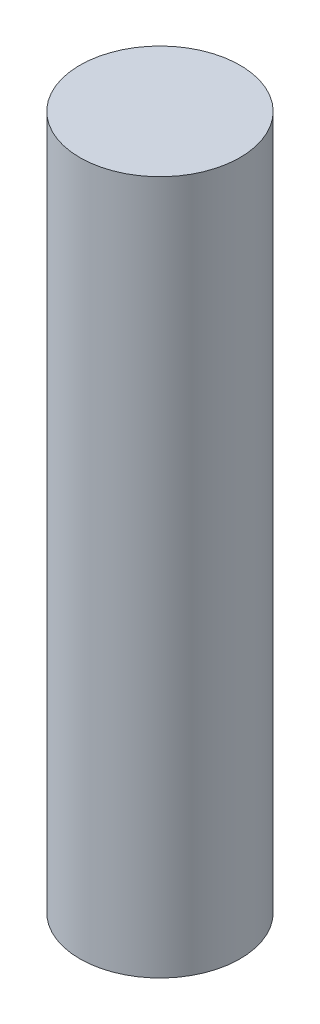
SolidWorks part; units mm, degrees
ref_plane "Alzado" through (0, 0, 0) normal (0, 0, 1) x (1, 0, 0)
ref_plane "Planta" through (0, 0, 0) normal (0, 1, 0) x (1, 0, 0)
ref_plane "Vista lateral" through (0, 0, 0) normal (1, 0, 0) x (0, 0, -1)
sketch "Croquis1" plane through (0, 0, 0) normal (0, 1, 0) x (1, 0, 0)
  circle A0 centre (0, 0) radius 1.5
  dimension "D1" = 3
extrude "Saliente-Extruir1" add sketch "Croquis1" along normal blind 13
